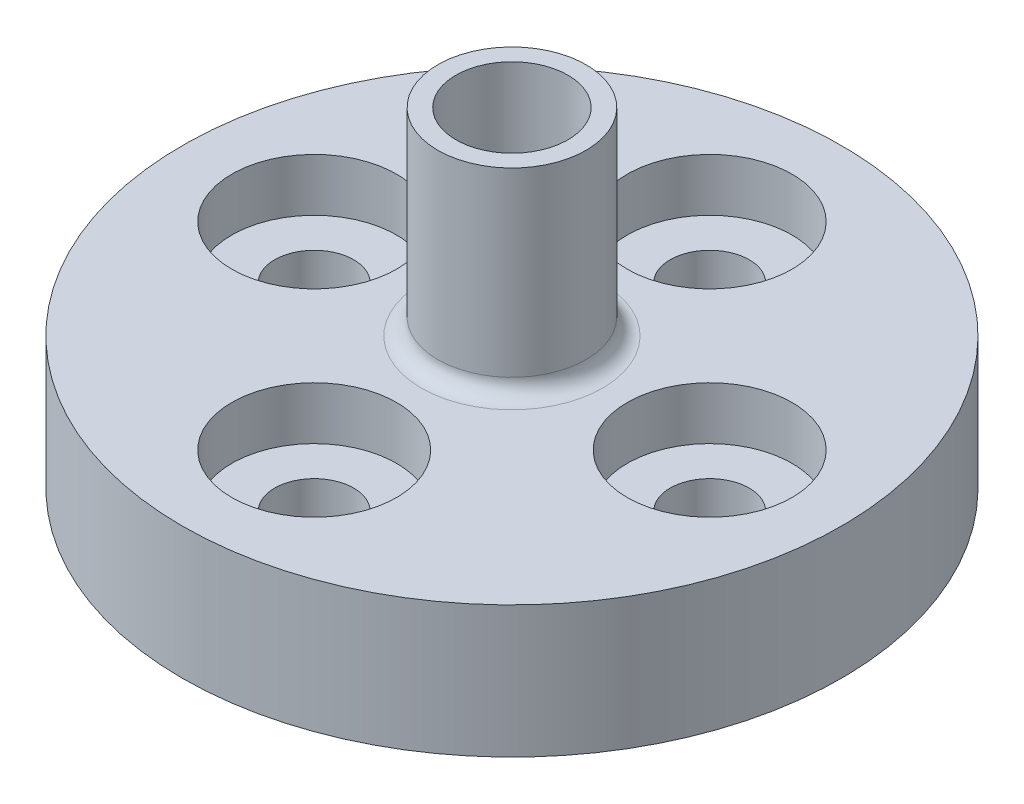
SolidWorks part; units mm, degrees
ref_plane "Front Plane" through (0, 0, 0) normal (0, 0, 1) x (1, 0, 0)
ref_plane "Top Plane" through (0, 0, 0) normal (0, 1, 0) x (1, 0, 0)
ref_plane "Right Plane" through (0, 0, 0) normal (1, 0, 0) x (0, 0, -1)
sketch "Sketch1" plane through (0, 0, 0) normal (0, 1, 0) x (1, 0, 0)
  circle A0 centre (0, 0) radius 10
  dimension "D1" = 20
extrude "Boss-Extrude1" add sketch "Sketch1" along normal blind 4
sketch "Sketch2" plane through (0, 4, 0) normal (0, 1, 0) x (1, 0, 0)
  circle A0 centre (6, 0) radius 1.2
  point P0 (6, 0)
  dimension "D1" = 2.4
  dimension "D2" = 6
hole_wizard "CBORE for M2 Pan Head Screw1" positions "Sketch2" profile "Sketch3" counterbore size "M2" standard "DIN" end condition through all
sketch "Sketch3" plane through (6, 4, 0) normal (1, 0, 0) x (0, 0, 1)
  line L0 (0, 0) -> (0, 4)
  line L1 (0, 4) -> (1.2, 4)
  line L3 (1.2, 4) -> (1.2, 1.6)
  line L4 (1.2, 1.6) -> (2.5, 1.6)
  line L5 (2.5, 1.6) -> (2.5, 0)
  line L7 (2.5, 0) -> (0, 0)
  line L11 (0, -6.35) -> (0, 107.95) construction
  dimension "Thru Hole Dia." = 2.4
  dimension "Thru Hole Depth" = 4
  dimension "C'Bore Dia." = 5
  dimension "C'Bore Depth" = 1.6
sketch "Sketch4" plane through (0, 4, 0) normal (0, 1, 0) x (1, 0, 0)
  circle A0 centre (0, 0) radius 2.25
  dimension "D1" = 4.5
extrude "Boss-Extrude2" add sketch "Sketch4" along normal blind 6
pattern_circular "CirPattern1" count 4 over 360 about axis through (0, 0, 0) along (0, 1, 0) of "CBORE for M2 Pan Head Screw1"
sketch "Sketch5" plane through (0, 0, 0) normal (0, -1, 0) x (1, 0, 0)
  circle A0 centre (0, 0) radius 1.6
  point P0 (0, 0)
  dimension "D1" = 3.2
hole_wizard "CSK for M3 Countersunk Flat Head Screw1" positions "Sketch5" profile "Sketch6" countersink size "M3" standard "DIN" end condition through all
sketch "Sketch6" plane through (0, 0, 0) normal (1, 0, 0) x (0, 0, -1)
  line L0 (0, 0) -> (0, 10)
  line L1 (0, 10) -> (1.7, 10)
  line L2 (1.7, 10) -> (1.7, 1.45)
  line L3 (1.7, 1.45) -> (3.15, 0)
  line L5 (3.15, 0) -> (0, 0)
  line L6 (-1.7, 1.45) -> (-3.15, 0) construction
  line L11 (0, -6.35) -> (0, 107.95) construction
  dimension "Thru Hole Dia." = 3.4
  dimension "Thru Hole Depth" = 10
  dimension "Near C'Sink Dia." = 6.3
  dimension "Near C'Sink Angle" = 90
fillet "Fillet1" radius 0.5 1 edges at (0, 4, 2.25)
